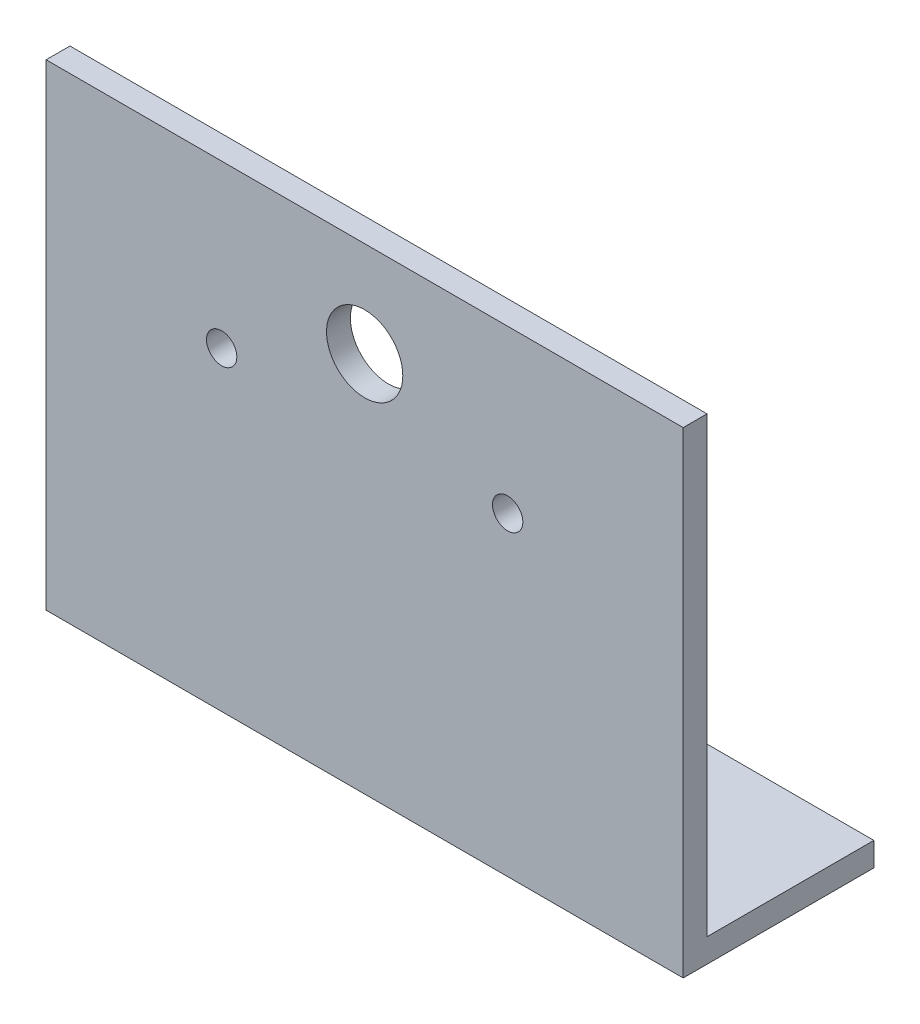
SolidWorks part; units mm, degrees
ref_plane "Front Plane" through (0, 0, 0) normal (0, 0, 1) x (1, 0, 0)
ref_plane "Top Plane" through (0, 0, 0) normal (0, 1, 0) x (1, 0, 0)
ref_plane "Right Plane" through (0, 0, 0) normal (1, 0, 0) x (0, 0, -1)
sketch "Sketch1" plane through (0, 0, 0) normal (0, 0, 1) x (1, 0, 0)
  line L1 (42.4335, 21.59) -> (-42.4335, 21.59)
  line L2 (42.4335, 21.59) -> (42.4335, -41.91)
  line L3 (42.4335, -41.91) -> (-42.4335, -41.91)
  line L4 (-42.4335, 21.59) -> (-42.4335, -41.91)
  line L5 (0, 0) -> (0, 8.89) construction
  circle A0 centre (0, 8.89) radius 5.08
  point P0 (0, 0)
extrude "Boss-Extrude1" add sketch "Sketch1" along normal blind 3.175
hole_wizard "#10-32 Tapped Hole1" positions "Sketch5" profile "Sketch4" tap size "#10-32" standard "Ansi Inch"
sketch "Sketch5" plane through (0, 0, 3.175) normal (0, 0, 1) x (1, 0, 0)
  line L0 (0, 0) -> (-19.05, 0)
  line L2 (0, 0) -> (19.05, 0)
  point P0 (-19.05, 0)
sketch "Sketch4" plane through (-19.05, 0, 3.175) normal (1, 0, 0) x (0, -1, 0)
  line L0 (0, 0) -> (0, 13.1513)
  line L1 (0, 13.1513) -> (2.0193, 11.938)
  line L2 (2.0193, 11.938) -> (2.0193, 0)
  line L5 (2.0193, 0) -> (0, 0)
  line L10 (0, 13.1513) -> (-2.0193, 11.938) construction
  line L11 (0, -6.35) -> (0, 107.95) construction
  dimension "Tap Drill Dia." = 4.0386
  dimension "Tap Drill Depth" = 11.938
  dimension "Drill Angle" = 118
cosmetic thread "Hole Thread1" parameters "D1"=3.175, "D2"=4.826
hole_wizard "#10-32 Tapped Hole2" positions "Sketch7" profile "Sketch6" tap size "#10-32" standard "Ansi Inch"
sketch "Sketch7" plane through (0, 0, 3.175) normal (0, 0, 1) x (1, 0, 0)
  point P0 (19.05, 0)
sketch "Sketch6" plane through (19.05, 0, 3.175) normal (1, 0, 0) x (0, -1, 0)
  line L0 (0, 0) -> (0, 13.1513)
  line L1 (0, 13.1513) -> (2.0193, 11.938)
  line L2 (2.0193, 11.938) -> (2.0193, 0)
  line L5 (2.0193, 0) -> (0, 0)
  line L10 (0, 13.1513) -> (-2.0193, 11.938) construction
  line L11 (0, -6.35) -> (0, 107.95) construction
  dimension "Tap Drill Dia." = 4.0386
  dimension "Tap Drill Depth" = 11.938
  dimension "Drill Angle" = 118
cosmetic thread "Hole Thread2" parameters "D1"=3.175, "D2"=4.826
sketch "Sketch10" plane through (0, 0, 0) normal (0, 0, -1) x (-1, 0, 0)
  line L0 (42.4335, 21.59) -> (42.4335, -41.91) construction
  line L1 (-42.4335, -41.91) -> (42.4335, -41.91)
  line L2 (-42.4335, -41.91) -> (-42.4335, -38.735)
  line L3 (-42.4335, -38.735) -> (42.4335, -38.735)
  line L4 (42.4335, -41.91) -> (42.4335, -38.735)
extrude "Boss-Extrude2" add sketch "Sketch10" along normal blind 22.225
hole_wizard "#10-32 Tapped Hole3" positions "Sketch12" profile "Sketch11" tap size "#10-32" standard "Ansi Inch"
sketch "Sketch12" plane through (0, -38.735, 0) normal (0, 1, 0) x (-1, 0, 0)
  point P0 (19.05, -17.78)
sketch "Sketch11" plane through (-19.05, -38.735, -17.78) normal (1, 0, 0) x (0, 0, 1)
  line L0 (0, 0) -> (0, 13.1513)
  line L1 (0, 13.1513) -> (2.0193, 11.938)
  line L2 (2.0193, 11.938) -> (2.0193, 0)
  line L5 (2.0193, 0) -> (0, 0)
  line L10 (0, 13.1513) -> (-2.0193, 11.938) construction
  line L11 (0, -6.35) -> (0, 107.95) construction
  dimension "Tap Drill Dia." = 4.0386
  dimension "Tap Drill Depth" = 11.938
  dimension "Drill Angle" = 118
cosmetic thread "Hole Thread3" parameters "D1"=3.175, "D2"=4.826
hole_wizard "#10-32 Tapped Hole4" positions "Sketch14" profile "Sketch13" tap size "#10-32" standard "Ansi Inch"
sketch "Sketch14" plane through (0, -38.735, 0) normal (0, 1, 0) x (-1, 0, 0)
  point P0 (-19.05, -17.78)
sketch "Sketch13" plane through (19.05, -38.735, -17.78) normal (1, 0, 0) x (0, 0, 1)
  line L0 (0, 0) -> (0, 13.1513)
  line L1 (0, 13.1513) -> (2.0193, 11.938)
  line L2 (2.0193, 11.938) -> (2.0193, 0)
  line L5 (2.0193, 0) -> (0, 0)
  line L10 (0, 13.1513) -> (-2.0193, 11.938) construction
  line L11 (0, -6.35) -> (0, 107.95) construction
  dimension "Tap Drill Dia." = 4.0386
  dimension "Tap Drill Depth" = 11.938
  dimension "Drill Angle" = 118
cosmetic thread "Hole Thread4" parameters "D1"=3.175, "D2"=4.826
